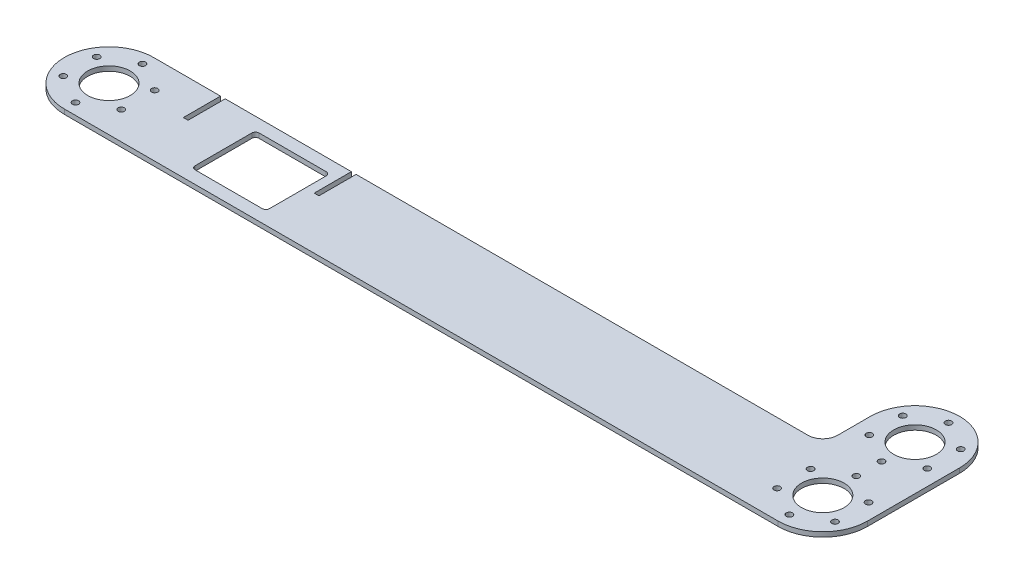
SolidWorks part; units mm, degrees
material "ASTM A36 Steel"
ref_plane "Alzado" through (0, 0, 0) normal (0, 0, 1) x (1, 0, 0)
ref_plane "Planta" through (0, 0, 0) normal (0, 1, 0) x (1, 0, 0)
ref_plane "Vista lateral" through (0, 0, 0) normal (1, 0, 0) x (0, 0, -1)
sketch "Sketch1" plane through (0, 0, 0) normal (0, 1, 0) x (1, 0, 0)
  line L0 (277.7419, -0.9677) -> (277.7419, 61.0323)
  line L1 (-232.2581, -30.9677) -> (247.7419, -30.9677)
  line L3 (-232.2581, 29.0323) -> (207.7419, 29.0323)
  line L5 (-232.2581, -30.9677) -> (217.7419, 29.0323) construction
  line L6 (-232.2581, 29.0323) -> (247.7419, -30.9677) construction
  line L11 (217.7419, 61.0323) -> (217.7419, 39.0323)
  arc A0 (-232.2581, 29.0323) -> (-232.2581, -30.9677) centre (-232.2581, -0.9677) ccw
  arc A2 (247.7419, -30.9677) -> (277.7419, -0.9677) centre (247.7419, -0.9677) ccw
  arc A3 (277.7419, 61.0323) -> (217.7419, 61.0323) centre (247.7419, 61.0323) ccw
  arc A4 (207.7419, 29.0323) -> (217.7419, 39.0323) centre (207.7419, 39.0323) ccw
  point P0 (0, 0)
  dimension "D1" = 60
  dimension "D2" = 30
  dimension "D5" = 10
  dimension "D3" = 480
  dimension "D4" = 62
extrude "Boss-Extrude1" add sketch "Sketch1" along normal blind 3.175
sketch "Sketch2" plane through (0, 3.175, 0) normal (0, 1, 0) x (1, 0, 0)
  circle A0 centre (-232.2581, -0.9677) radius 14.3
  circle A1 centre (247.7419, -0.9677) radius 14.3
  circle A2 centre (247.7419, 61.0323) radius 14.3
  dimension "D1" = 28.6
sketch "Sketch3" plane through (0, 3.175, 0) normal (0, 1, 0) x (1, 0, 0)
  line L0 (247.7419, 91.0323) -> (-232.2581, 91.0323)
  line L1 (-232.2581, 31.0323) -> (247.7419, 31.0323)
  arc A0 (247.7419, 31.0323) -> (247.7419, 91.0323) centre (247.7419, 61.0323) ccw
  arc A1 (-232.2581, 91.0323) -> (-232.2581, 31.0323) centre (-232.2581, 61.0323) ccw
  arc A2 (277.7419, 61.0323) -> (217.7419, 61.0323) centre (247.7419, 61.0323) ccw construction
extrude "Cut-Extrude1" cut sketch "Sketch2" against normal through all
sketch "Sketch4" plane through (0, 3.175, 0) normal (0, 1, 0) x (1, 0, 0)
  line L0 (0, -29.0323) -> (0, 29.0323) construction
  line L1 (207.7419, 29.0323) -> (-232.2581, 29.0323) construction
  circle A0 centre (-232.2581, -0.9677) radius 22.5 construction
  circle A1 centre (-232.2581, 21.5323) radius 2.1
  circle A2 centre (-212.7725, 10.2823) radius 2.1
  circle A3 centre (-212.7725, -12.2177) radius 2.1
  circle A4 centre (-232.2581, -23.4677) radius 2.1
  circle A5 centre (247.7419, -0.9677) radius 22.5 construction
  circle A6 centre (247.7419, 61.0323) radius 22.5 construction
  circle A7 centre (247.7419, 83.5323) radius 2.1
  circle A8 centre (247.7419, 21.5323) radius 2.1
  circle A9 centre (267.2275, 72.2823) radius 2.1
  circle A10 centre (267.2275, 49.7823) radius 2.1
  circle A11 centre (247.7419, 38.5323) radius 2.1
  circle A12 centre (267.2275, 10.2823) radius 2.1
  circle A13 centre (267.2275, -12.2177) radius 2.1
  circle A14 centre (247.7419, -23.4677) radius 2.1
  circle A15 centre (-251.7436, -12.2177) radius 2.1
  circle A16 centre (-251.7436, 10.2823) radius 2.1
  circle A17 centre (228.2564, -12.2177) radius 2.1
  circle A18 centre (228.2564, 10.2823) radius 2.1
  circle A19 centre (228.2564, 49.7823) radius 2.1
  circle A20 centre (228.2564, 72.2823) radius 2.1
  point P14 (-232.2581, -0.9677)
  point P19 (0, 0)
  point P38 (247.7419, 61.0323)
  point P45 (247.7419, -0.9677)
  dimension "D1" = 45
  dimension "D2" = 4.2
  dimension "D4" = 6
  dimension "D3" = 6
  dimension "D5" = 6
extrude "Cut-Extrude2" cut sketch "Sketch4" against normal through all
sketch "Sketch5" plane through (0, 3.175, 0) normal (0, 1, 0) x (1, 0, 0)
  line L0 (-232.2581, -0.9677) -> (-126.7581, -0.9677) construction
  line L1 (-126.7581, -0.9677) -> (-86.7581, -0.9677) construction
  circle A0 centre (-126.7581, -0.9677) radius 15 construction
  dimension "D1" = 30
  dimension "D2" = 105.5
  dimension "D3" = 40
sketch "Sketch6" plane through (0, 3.175, 0) normal (0, 1, 0) x (1, 0, 0)
  line L0 (207.7419, 29.0323) -> (-232.2581, 29.0323) construction
  line L1 (-187.2581, 29.0323) -> (-184.0831, 29.0323)
  line L2 (-187.2581, 29.0323) -> (-187.2581, 4.0323)
  line L3 (-187.2581, 4.0323) -> (-184.0831, 4.0323)
  line L4 (-184.0831, 29.0323) -> (-184.0831, 4.0323)
  line L5 (-187.2581, 29.0323) -> (-184.0831, 4.0323) construction
  line L6 (-187.2581, 4.0323) -> (-184.0831, 29.0323) construction
  line L9 (-232.2581, -0.9677) -> (-126.7581, -0.9677) construction
  point P4 (-185.6706, 16.5323)
  dimension "D1" = 3.175
  dimension "D2" = 45
  dimension "D3" = 5
extrude "Cut-Extrude3" cut sketch "Sketch6" against normal blind 10
sketch "Sketch7" [suppressed] plane through (0, 3.175, 0) normal (0, 1, 0) x (1, 0, 0)
  line L0 (-126.7581, -0.9677) -> (-132.7581, -0.9677) construction
  line L1 (-232.2581, -0.9677) -> (-126.7581, -0.9677) construction
  line L2 (-126.7581, -15.9677) -> (-132.7581, -15.9677)
  line L3 (-126.7581, 14.0323) -> (-132.7581, 14.0323)
  circle A0 centre (-126.7581, -0.9677) radius 15 construction
  arc A1 (-126.7581, -15.9677) -> (-126.7581, 14.0323) centre (-126.7581, -0.9677) ccw
  arc A2 (-132.7581, 14.0323) -> (-132.7581, -15.9677) centre (-132.7581, -0.9677) ccw
  point P3 (-129.7581, -0.9677)
  dimension "D1" = 30
  dimension "D3" = 6
extrude "Cut-Extrude4" [suppressed] cut sketch "Sketch7" against normal blind 10
sketch "Sketch9" plane through (0, 3.175, 0) normal (0, 1, 0) x (1, 0, 0)
  line L1 (-148.2581, -22.4677) -> (-107.6897, -22.4677)
  line L3 (-148.2581, 20.5323) -> (-107.6897, 20.5323)
  line L4 (-105.2581, -20.0361) -> (-105.2581, 18.1006)
  line L5 (-148.2581, -22.4677) -> (-105.2581, 20.5323) construction
  line L6 (-148.2581, 20.5323) -> (-105.2581, -22.4677) construction
  line L7 (-148.2581, 20.5323) -> (-152.8264, 20.5323)
  line L9 (-148.2581, -22.4677) -> (-152.8264, -22.4677)
  line L10 (-155.2581, 18.1006) -> (-155.2581, -20.0361)
  line L11 (-148.2581, 20.5323) -> (-155.2581, -22.4677) construction
  line L12 (-148.2581, -22.4677) -> (-155.2581, 20.5323) construction
  arc A0 (-152.8264, 20.5323) -> (-155.2581, 18.1006) centre (-152.8264, 18.1006) ccw
  arc A1 (-152.8264, -22.4677) -> (-155.2581, -20.0361) centre (-152.8264, -20.0361) cw
  arc A2 (-107.6897, -22.4677) -> (-105.2581, -20.0361) centre (-107.6897, -20.0361) ccw
  arc A3 (-107.6897, 20.5323) -> (-105.2581, 18.1006) centre (-107.6897, 18.1006) cw
  point P0 (-126.7581, -0.9677)
  point P9 (-151.7581, -0.9677)
  dimension "D4" = 2.4316
  dimension "D1" = 43
  dimension "D2" = 43
  dimension "D3" = 7
extrude "Cut-Extrude6" cut sketch "Sketch9" against normal blind 10 contours L7 L10 L9 L1 L4 L3
sketch "Sketch10" plane through (0, 3.175, 0) normal (0, 1, 0) x (1, 0, 0)
  line L1 (-99.2581, 29.0323) -> (-96.0831, 29.0323)
  line L2 (-99.2581, 29.0323) -> (-99.2581, 4.0323)
  line L3 (-99.2581, 4.0323) -> (-96.0831, 4.0323)
  line L4 (-96.0831, 29.0323) -> (-96.0831, 4.0323)
  line L5 (-99.2581, 29.0323) -> (-96.0831, 4.0323) construction
  line L6 (-99.2581, 4.0323) -> (-96.0831, 29.0323) construction
  line L7 (-187.2581, 4.0323) -> (-184.0831, 4.0323) construction
  line L8 (207.7419, 29.0323) -> (-184.0831, 29.0323) construction
  line L9 (-105.2581, -20.0361) -> (-105.2581, 18.1006) construction
  point P4 (-97.6706, 16.5323)
  point P10 (0, 0)
  dimension "D1" = 6
extrude "Cut-Extrude7" cut sketch "Sketch10" against normal blind 6.35
